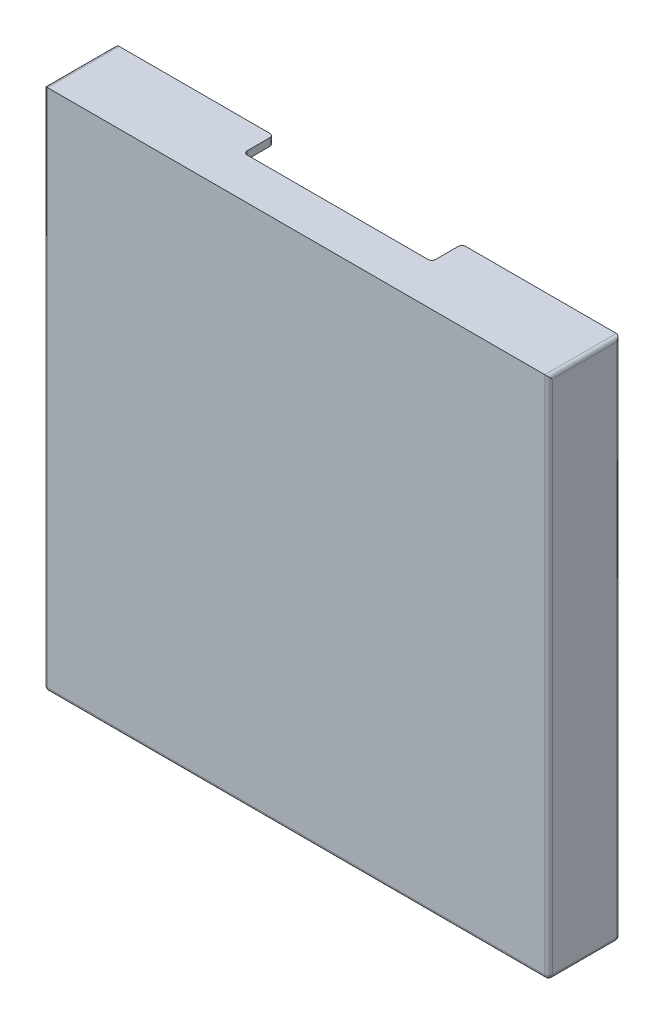
SolidWorks part; units mm, degrees
ref_plane "前视基准面" through (0, 0, 0) normal (0, 0, 1) x (1, 0, 0)
ref_plane "上视基准面" through (0, 0, 0) normal (0, 1, 0) x (1, 0, 0)
ref_plane "右视基准面" through (0, 0, 0) normal (1, 0, 0) x (0, 0, -1)
sketch "草图1" plane through (0, 0, 0) normal (0, 1, 0) x (1, 0, 0)
  line L1 (134, -19) -> (-134, -19)
  line L2 (134, -19) -> (134, 19)
  line L3 (134, 19) -> (-134, 19)
  line L4 (-134, -19) -> (-134, 19)
  line L5 (134, -19) -> (-134, 19) construction
  line L6 (134, 19) -> (-134, -19) construction
  point P0 (0, 0)
  dimension "D1" = 268
  dimension "D2" = 38
extrude "凸台-拉伸1" add sketch "草图1" along normal blind 278
sketch "草图2" plane through (0, 0, -19) normal (0, 0, -1) x (-1, 0, 0)
  line L14 (-130, 4) -> (130, 4)
  line L15 (130, 4) -> (130, 274)
  line L16 (130, 274) -> (-130, 274)
  line L17 (-130, 274) -> (-130, 4)
  line L18 (-130, 4) -> (130, 4)
  line L19 (130, 4) -> (130, 274)
  line L20 (130, 274) -> (-130, 274)
  line L21 (-130, 274) -> (-130, 4)
  dimension "D1" = 4
extrude "切除-拉伸1" cut sketch "草图2" against normal offset from surface (36 mm away) 2 up to face at (0, 139, 19)
sketch "草图3" plane through (0, 278, 0) normal (0, 1, 0) x (1, 0, 0)
  line L0 (0, 19) -> (0, -19) construction
  line L1 (134, 19) -> (-134, 19) construction
  line L2 (-134, -19) -> (134, -19) construction
  line L3 (50, 19) -> (-50, 19)
  line L4 (-50, 19) -> (-50, 3)
  line L5 (-50, 3) -> (50, 3)
  line L6 (50, 19) -> (50, 3)
  point P10 (0, 3)
  dimension "D1" = 16
  dimension "D2" = 100
extrude "切除-拉伸2" cut sketch "草图3" against normal up to next
fillet "圆角1" radius 2 14 edges at (134, 278, 0) (134, 0, 0) (-134, 0, 0) (-134, 278, 0) (0, 0, -19) (134, 139, -19) (-134, 139, -19) (0, 0, 19) (134, 139, 19) (-134, 139, 19) (-50, 276, -3) (50, 276, -3) (50, 276, -19) (-50, 276, -19)
